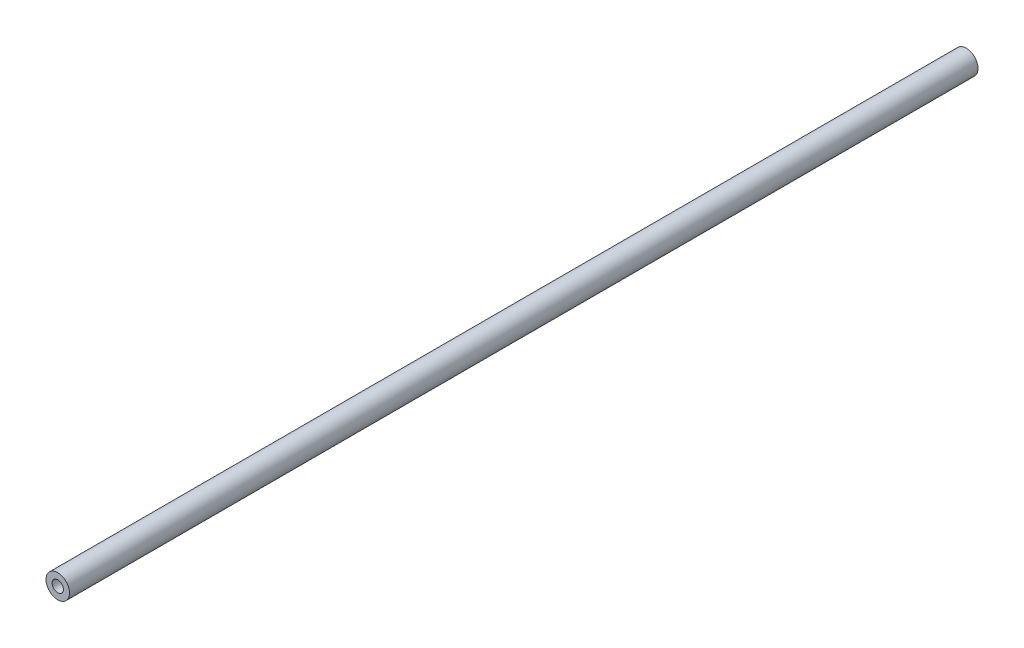
SolidWorks part; units mm, degrees
ref_plane "Front" through (0, 0, 0) normal (0, 0, 1) x (1, 0, 0)
ref_plane "Top" through (0, 0, 0) normal (0, 1, 0) x (1, 0, 0)
ref_plane "Right" through (0, 0, 0) normal (1, 0, 0) x (0, 0, -1)
sketch "Sketch1" plane through (0, 0, 0) normal (0, 0, 1) x (1, 0, 0)
  circle A0 centre (0, 0) radius 0.1524
  circle A1 centre (0, 0) radius 0.3175
  dimension "D1" = 0.3048
  dimension "D2" = 0.635
extrude "Boss-Extrude1" add sketch "Sketch1" along normal blind 24.511
